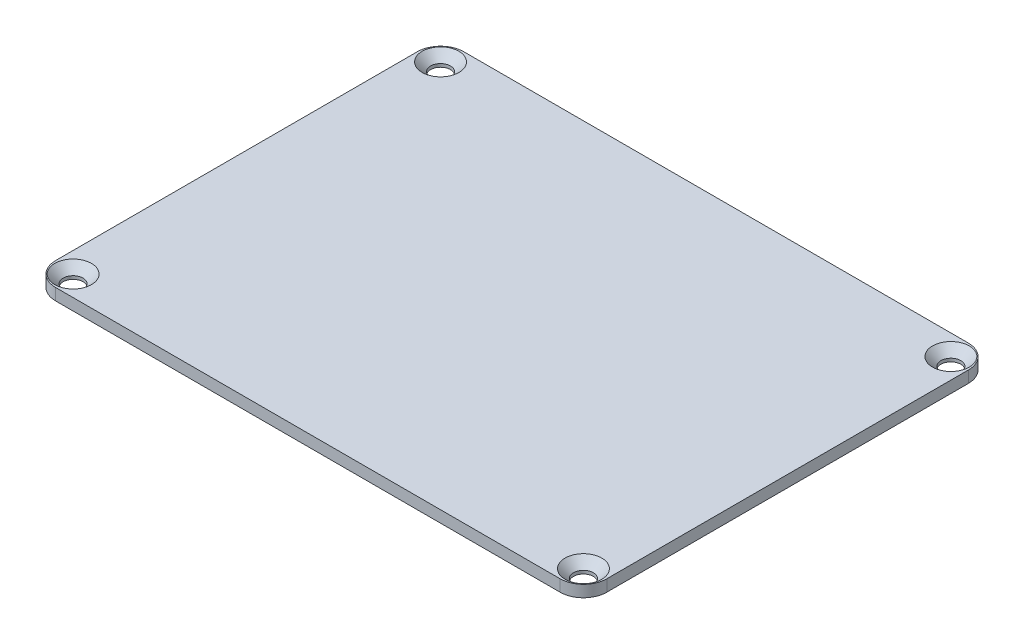
SolidWorks part; units mm, degrees
ref_plane "Front Plane" through (0, 0, 0) normal (0, 0, 1) x (1, 0, 0)
ref_plane "Top Plane" through (0, 0, 0) normal (0, 1, 0) x (1, 0, 0)
ref_plane "Right Plane" through (0, 0, 0) normal (1, 0, 0) x (0, 0, -1)
sketch "Sketch1" plane through (0, 0, 0) normal (0, 1, 0) x (1, 0, 0)
  line L1 (-47.25, 35) -> (47.25, 35)
  line L2 (-47.25, 35) -> (-47.25, -35)
  line L3 (-47.25, -35) -> (47.25, -35)
  line L4 (47.25, 35) -> (47.25, -35)
  line L5 (-47.25, 35) -> (47.25, -35) construction
  line L6 (-47.25, -35) -> (47.25, 35) construction
  point P0 (0, 0)
  dimension "D1" = 70
  dimension "D2" = 94.5
extrude "Boss-Extrude1" add sketch "Sketch1" against normal blind 2
sketch "Sketch2" plane through (0, 0, 0) normal (0, 1, 0) x (1, 0, 0)
  line L0 (-47.25, 35) -> (-47.25, -35) construction
  line L1 (47.25, 35) -> (-47.25, 35) construction
  line L2 (0, 0) -> (0, 50.526) construction
  line L3 (0, 0) -> (-66.4116, 0) construction
  point P0 (-43.75, 31.5)
  point P10 (43.75, 31.5)
  point P11 (43.75, -31.5)
  point P12 (-43.75, -31.5)
  dimension "D1" = 3.5
  dimension "D2" = 3.5
hole_wizard "CSK for M3 Flat Head Machine Screw1" positions "3DSketch1" profile "Sketch3" countersink size "M3" standard "ANSI Metric"
sketch3d "3DSketch1"
  point P0 (-43.75, 0, -31.5)
  point P3 (43.75, 0, -31.5)
  point P6 (43.75, 0, 31.5)
  point P9 (-43.75, 0, 31.5)
sketch "Sketch3" plane through (-43.75, 0, -31.5) normal (1, 0, 0) x (0, 0, 1)
  line L0 (0, 0) -> (0, 31.0215)
  line L1 (0, 31.0215) -> (1.7, 30)
  line L2 (1.7, 30) -> (1.7, 1.45)
  line L3 (1.7, 1.45) -> (3.15, 0)
  line L5 (3.15, 0) -> (0, 0)
  line L6 (-1.7, 1.45) -> (-3.15, 0) construction
  line L10 (0, 31.0215) -> (-1.7, 30) construction
  line L11 (0, -6.35) -> (0, 107.95) construction
  dimension "Hole Dia." = 3.4
  dimension "Hole Depth" = 30
  dimension "Near C'Sink Dia." = 6.3
  dimension "Near C'Sink Angle" = 90
  dimension "Drill Angle" = 118
fillet "Fillet1" radius 4 4 edges at (-47.25, -1, -35) (47.25, -1, -35) (47.25, -1, 35) (-47.25, -1, 35)
